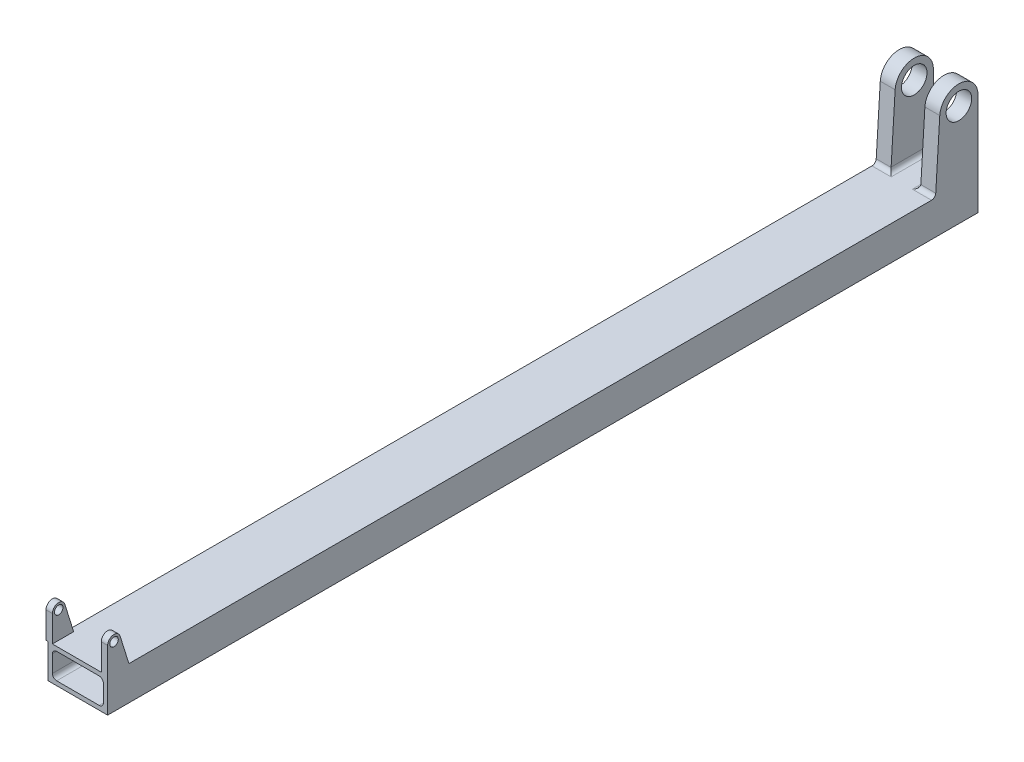
SolidWorks part; units mm, degrees
material "AISI 1045 Steel, cold drawn"
ref_plane "Front Plane" through (0, 0, 0) normal (0, 0, 1) x (1, 0, 0)
ref_plane "Top Plane" through (0, 0, 0) normal (0, 1, 0) x (1, 0, 0)
ref_plane "Right Plane" through (0, 0, 0) normal (1, 0, 0) x (0, 0, -1)
sketch "Sketch1" plane through (0, 0, 0) normal (1, 0, 0) x (0, 0, -1)
  line L0 (0, 0) -> (-2600, 0)
  line L1 (-2600, 0) -> (-2600, 101.6)
  line L2 (-2600, 101.6) -> (0, 101.6)
  line L3 (0, 101.6) -> (0, 0)
  line L4 (0, 101.6) -> (0, 304.8)
  line L5 (-114.1906, 308.3343) -> (-127, 101.6)
  arc A0 (0, 304.8) -> (-114.1906, 308.3343) centre (-57.15, 304.8) ccw
  circle A1 centre (-57.15, 304.8) radius 38.1
  dimension "D1" = 101.6
  dimension "D4" = 76.2
  dimension "D2" = 2600
  dimension "D3" = 203.2
  dimension "D5" = 19.05
  dimension "D6" = 69.85
sketch "Sketch2" plane through (0, 0, 0) normal (0, 0, 1) x (1, 0, 0)
  line L0 (0, 101.6) -> (0, 0) construction
  line L1 (0, 101.6) -> (-177.8, 101.6)
  line L2 (0, 101.6) -> (0, 0)
  line L3 (0, 0) -> (-177.8, 0)
  line L4 (-177.8, 101.6) -> (-177.8, 0)
  line L5 (0, 101.6) -> (0, 304.8) construction
  line L6 (-12.7, 88.9) -> (-12.7, 12.7)
  line L7 (-12.7, 12.7) -> (-165.1, 12.7)
  line L8 (-165.1, 88.9) -> (-165.1, 12.7)
  line L9 (-12.7, 88.9) -> (-165.1, 88.9)
  dimension "D1" = 101.6
  dimension "D2" = 177.8
  dimension "D3" = 12.7
extrude "Boss-Extrude2" add sketch "Sketch2" along normal up to vertex (2600 mm away) up to point (0, 101.6, 2600)
extrude "Boss-Extrude3" add sketch "Sketch1" against normal blind 44.45 contours L4 A0 L5 L2 A1
ref_plane "Plane1" through (-177.8, 0, 0) normal (-1, 0, 0) x (0, 0, 1)
sketch "Sketch3" plane through (-177.8, 0, 0) normal (-1, 0, 0) x (0, 0, 1)
  line L3 (0, 304.8) -> (0, 101.6)
  line L4 (0, 101.6) -> (127, 101.6)
  line L5 (127, 101.6) -> (114.1906, 308.3343)
  line L6 (0, 304.8) -> (0, 101.6)
  line L7 (0, 101.6) -> (127, 101.6)
  line L8 (127, 101.6) -> (114.1906, 308.3343)
  circle A0 centre (57.15, 304.8) radius 38.1 construction
  arc A1 (114.1906, 308.3343) -> (0, 304.8) centre (57.15, 304.8) ccw
  arc A2 (114.1906, 308.3343) -> (0, 304.8) centre (57.15, 304.8) ccw
  circle A3 centre (57.15, 304.8) radius 38.1
  dimension "D1" = 0
extrude "Boss-Extrude5" add sketch "Sketch3" against normal blind 44.45
fillet "Fillet1" radius 12.7 4 edges at (-12.7, 12.7, 1300) (-12.7, 88.9, 1300) (-165.1, 88.9, 1300) (-165.1, 12.7, 1300)
fillet "Fillet2" radius 12.7 4 edges at (-155.575, 101.6, 127) (-22.225, 101.6, 127) (-133.35, 101.6, 63.5) (-44.45, 101.6, 63.5)
sketch "Sketch5" plane through (0, 0, 0) normal (1, 0, 0) x (0, 0, -1)
  line L0 (-2600, 101.6) -> (-2600, 180.34)
  line L1 (-2562.7601, 185.9996) -> (-2536.5, 101.6)
  line L2 (-2600, 101.6) -> (-138.9375, 101.6) construction
  line L3 (-2536.5, 101.6) -> (-2600, 101.6)
  arc A0 (-2600, 180.34) -> (-2562.7601, 185.9996) centre (-2580.95, 180.34) cw
  circle A1 centre (-2580.95, 180.34) radius 12.7
  dimension "D3" = 6.35
  dimension "D4" = 25.4
  dimension "D1" = 78.74
  dimension "D2" = 63.5
extrude "Boss-Extrude7" add sketch "Sketch5" against normal blind 19.05
pattern_linear "LPattern1" count 2 spacing 165.1 along (-1, 0, 0) of "Boss-Extrude7"
equation "\"D1@Sketch2\"=\"D1@Sketch1\""
